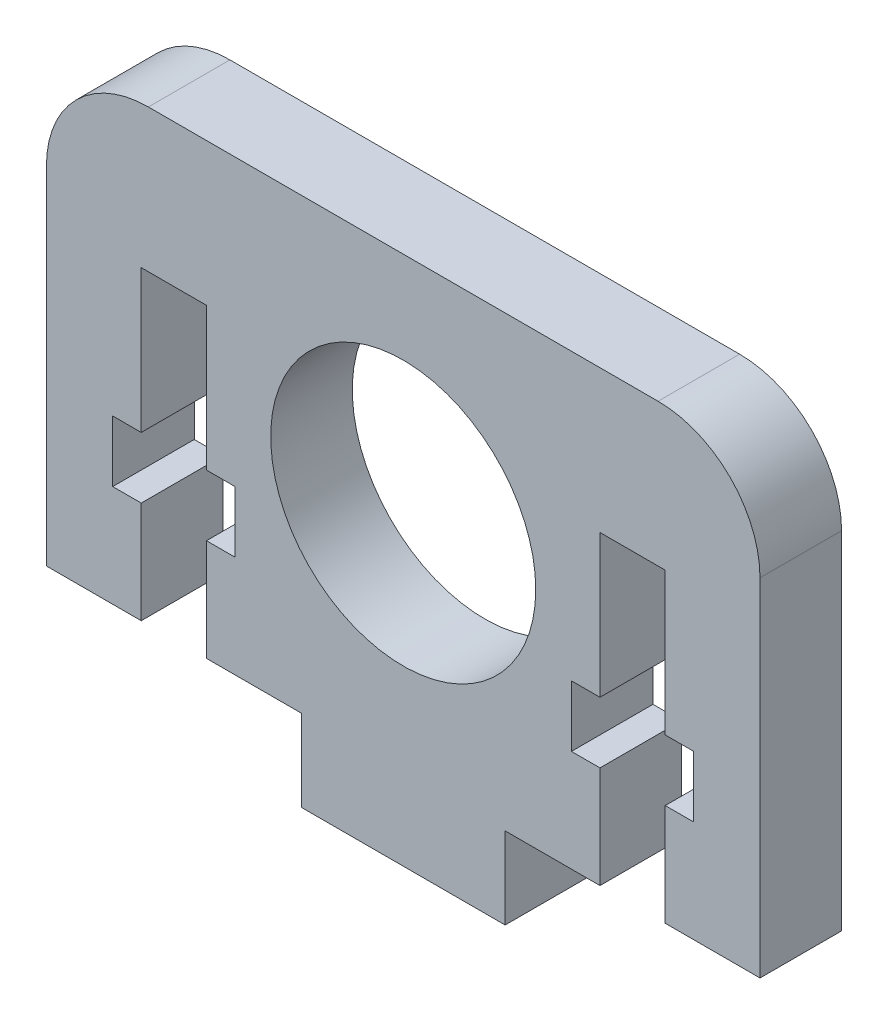
SolidWorks part; units mm, degrees
ref_plane "Front Plane" through (0, 0, 0) normal (0, 0, 1) x (1, 0, 0)
ref_plane "Top Plane" through (0, 0, 0) normal (0, 1, 0) x (1, 0, 0)
ref_plane "Right Plane" through (0, 0, 0) normal (1, 0, 0) x (0, 0, -1)
sketch "Sketch2" plane through (0, 0, 0) normal (0, 0, 1) x (1, 0, 0)
  line L0 (5, -11) -> (17.5, -11)
  line L1 (-17.5, 11) -> (17.5, 11)
  line L2 (-17.5, 11) -> (-17.5, -11)
  line L3 (-17.5, -11) -> (-5, -11)
  line L4 (17.5, 11) -> (17.5, -11)
  line L5 (-17.5, 11) -> (17.5, -11) construction
  line L6 (-17.5, -11) -> (17.5, 11) construction
  line L8 (-5, -11) -> (-5, -15)
  line L9 (-5, -15) -> (5, -15)
  line L10 (5, -11) -> (5, -15)
  circle A0 centre (0, 0) radius 6.5
  point P0 (0, 0)
  point P12 (0, -15)
  dimension "D4" = 13
  dimension "D1" = 35
  dimension "D2" = 10
  dimension "D3" = 4
  dimension "D5" = 11
extrude "Boss-Extrude1" add sketch "Sketch2" along normal blind 4
sketch "Sketch3" plane through (0, 0, 4) normal (0, 0, 1) x (1, 0, 0)
  line L0 (11.25, -11) -> (11.25, 4) construction
  line L1 (5, -11) -> (17.5, -11) construction
  line L2 (12.85, -11) -> (12.85, -6)
  line L3 (12.85, -6) -> (14.25, -6)
  line L4 (14.25, -6) -> (14.25, -3)
  line L5 (14.25, -3) -> (12.85, -3)
  line L6 (12.85, -3) -> (12.85, 4)
  line L7 (12.85, 4) -> (9.65, 4)
  line L8 (9.65, -3) -> (9.65, 4)
  line L9 (8.25, -3) -> (9.65, -3)
  line L10 (8.25, -6) -> (8.25, -3)
  line L11 (9.65, -6) -> (8.25, -6)
  line L12 (9.65, -11) -> (9.65, -6)
  line L13 (9.65, -11) -> (12.85, -11)
  line L14 (0, 11) -> (0, -15) construction
  line L15 (17.5, 11) -> (-17.5, 11) construction
  line L16 (-5, -15) -> (5, -15) construction
  line L17 (-11.25, -11) -> (-11.25, 4) construction
  line L18 (-9.65, -11) -> (-12.85, -11)
  line L19 (-9.65, -11) -> (-9.65, -6)
  line L20 (-9.65, -6) -> (-8.25, -6)
  line L21 (-8.25, -6) -> (-8.25, -3)
  line L22 (-8.25, -3) -> (-9.65, -3)
  line L23 (-9.65, -3) -> (-9.65, 4)
  line L24 (-12.85, 4) -> (-9.65, 4)
  line L25 (-12.85, -3) -> (-12.85, 4)
  line L26 (-14.25, -3) -> (-12.85, -3)
  line L27 (-14.25, -6) -> (-14.25, -3)
  line L28 (-12.85, -6) -> (-14.25, -6)
  line L29 (-12.85, -11) -> (-12.85, -6)
  dimension "D1" = 15
  dimension "D2" = 3.2
  dimension "D3" = 3
  dimension "D4" = 6
  dimension "D5" = 5
extrude "Cut-Extrude1" cut sketch "Sketch3" against normal through all
sketch "Sketch4" plane through (0, 0, 4) normal (0, 0, 1) x (1, 0, 0)
  line L0 (-5, -15) -> (5, -15) construction
  line L1 (-12.85, -11) -> (-17.5, -11)
  line L2 (-12.85, -11) -> (-12.85, -15)
  line L3 (-12.85, -15) -> (-17.5, -15)
  line L4 (-17.5, -11) -> (-17.5, -15)
  line L5 (12.85, -11) -> (17.5, -11)
  line L6 (12.85, -11) -> (12.85, -15)
  line L7 (12.85, -15) -> (17.5, -15)
  line L8 (17.5, -11) -> (17.5, -15)
  line L9 (17.5, -11) -> (17.5, 11) construction
  line L10 (-17.5, -11) -> (-12.85, -11) construction
extrude "Boss-Extrude2" [suppressed] add sketch "Sketch4" against normal blind 4 separate body
fillet "Fillet1" radius 5 2 edges at (-17.5, 11, 2) (17.5, 11, 2)
